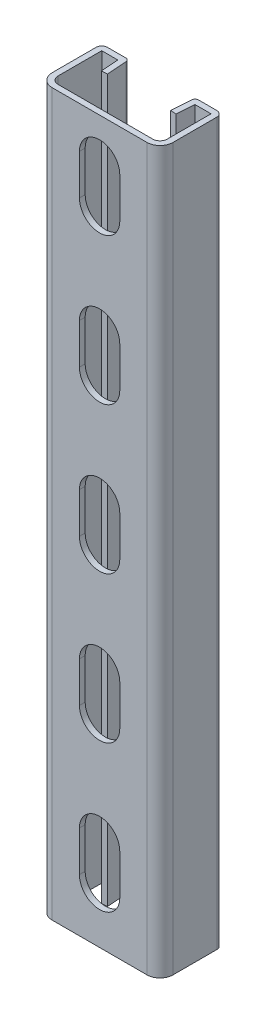
SolidWorks part; units mm, degrees
material "1023 Carbon Steel Sheet (SS)"
ref_plane "Front Plane" through (0, 0, 0) normal (0, 0, 1) x (1, 0, 0)
ref_plane "Top Plane" through (0, 0, 0) normal (0, 1, 0) x (1, 0, 0)
ref_plane "Right Plane" through (0, 0, 0) normal (1, 0, 0) x (0, 0, -1)
sketch "sk_profile" plane through (0, 0, 0) normal (0, 1, 0) x (1, 0, 0)
  line L0 (-20.95, -10.85) -> (20.95, -10.85) construction
  line L2 (20.95, -10.85) -> (20.95, 10.85) construction
  line L3 (20.95, 10.85) -> (11.5094, 10.85) construction
  line L4 (11.5094, 10.85) -> (10.95, 2.85) construction
  line L5 (0, -10.85) -> (0, 10.85) construction
  line L6 (18.95, 10.85) -> (12.6284, 10.85)
  line L7 (20.95, 8.85) -> (20.95, -6.35)
  line L8 (11.4314, 9.7337) -> (10.95, 2.85)
  line L9 (16.45, -10.85) -> (0, -10.85)
  arc A0 (20.95, 8.85) -> (18.95, 10.85) centre (18.95, 8.85) ccw
  arc A1 (16.45, -10.85) -> (20.95, -6.35) centre (16.45, -6.35) ccw
  arc A2 (12.6284, 10.85) -> (11.4314, 9.7337) centre (12.6284, 9.65) ccw
  point P2 (0, 0)
  dimension "D4" = 2
  dimension "D5" = 4.5
  dimension "D8" = 1.2
  dimension "D1" = 41.9
  dimension "D2" = 21.7
  dimension "D3" = 10
  dimension "D6" = 8
  dimension "D7" = 4
extrude "beam" add sketch "sk_profile" along normal blind 250 thin
mirror "mirror_half" about plane through (0, 0, 0) normal (1, 0, 0) of "beam"
sketch "Sketch4" plane through (0, 0, 0) normal (0, 0, 1) x (1, 0, 0)
  line L0 (0, 18.4) -> (0, 32.4) construction
  line L1 (0, -50) -> (0, 50) construction
  line L2 (-7, 18.4) -> (-7, 32.4)
  line L3 (7, 18.4) -> (7, 32.4)
  arc A0 (-7, 18.4) -> (7, 18.4) centre (0, 18.4) ccw
  arc A1 (7, 32.4) -> (-7, 32.4) centre (0, 32.4) ccw
  point P5 (0, 25.4)
  dimension "D1" = 7
  dimension "D2" = 14
  dimension "D3" = 25.4
extrude "punch" cut sketch "Sketch4" along normal through all
pattern_linear "pattern_punch" count 5 spacing 50.8 along (0, 1, 0) of "punch"
equation "\"radius_inside\"=3.5"
equation "\"r2\"=3"
equation "\"diam\"=51"
equation "\"chamf\"= 0.8"
equation "\"length\"= 250'length of channel"
equation "\"D1@beam\"=\"length\""
equation "\"thick\"= 2'steel thickness, 2mm measured for 14GA parts"
equation "\"D5@beam\"=\"thick\""
equation "\"n\"= \"length\" / 50'integer, number of holes"
equation "\"D1@pattern_punch\"=\"n\""
equation "\"offset_holes\"=25.4"
equation "\"D3@Sketch4\"=\"offset_holes\""
